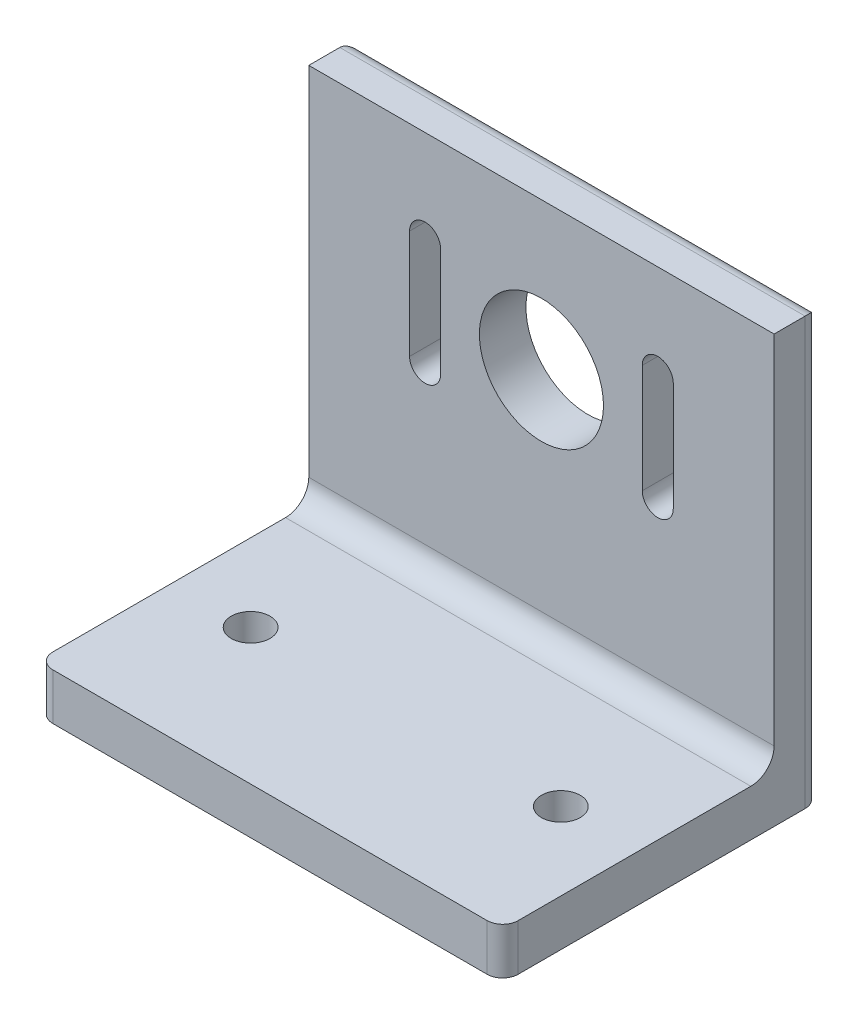
SolidWorks part; units mm, degrees
material "ABS"
ref_plane "Front Plane" through (0, 0, 0) normal (0, 0, 1) x (1, 0, 0)
ref_plane "Top Plane" through (0, 0, 0) normal (0, 1, 0) x (1, 0, 0)
ref_plane "Right Plane" through (0, 0, 0) normal (1, 0, 0) x (0, 0, -1)
sketch "Sketch2" plane through (0, 0, 0) normal (0, 1, 0) x (1, 0, 0)
  line L1 (-30, 17.5) -> (30, 17.5)
  line L2 (-30, 17.5) -> (-30, -17.5)
  line L3 (-30, -17.5) -> (30, -17.5)
  line L4 (30, 17.5) -> (30, -17.5)
  line L5 (-30, 17.5) -> (30, -17.5) construction
  line L6 (-30, -17.5) -> (30, 17.5) construction
  point P0 (0, 0)
  dimension "D1" = 60
  dimension "D2" = 35
extrude "Boss-Extrude1" add sketch "Sketch2" along normal blind 6
sketch "Sketch3" plane through (0, 0, -17.5) normal (0, 0, -1) x (-1, 0, 0)
  line L1 (-30, 0) -> (30, 0)
  line L2 (-30, 0) -> (-30, 55)
  line L3 (-30, 55) -> (30, 55)
  line L4 (30, 0) -> (30, 55)
  dimension "D1" = 60
  dimension "D2" = 55
extrude "Boss-Extrude2" add sketch "Sketch3" along normal blind 6
sketch "Sketch4" plane through (0, 0, -17.5) normal (0, 0, 1) x (1, 0, 0)
  line L0 (30, 6) -> (-30, 6) construction
  circle A0 centre (0, 36) radius 8
  point P4 (0, 6)
  dimension "D1" = 16
  dimension "D2" = 30
  dimension "D3" = 30
extrude "Cut-Extrude1" cut sketch "Sketch4" against normal through all
sketch "Sketch5" plane through (0, 0, -17.5) normal (0, 0, 1) x (1, 0, 0)
  line L0 (-15, 43) -> (-15, 29) construction
  line L1 (-13, 43) -> (-13, 29)
  line L2 (-17, 43) -> (-17, 29)
  line L3 (15, 43) -> (15, 29) construction
  line L4 (17, 43) -> (17, 29)
  line L5 (13, 43) -> (13, 29)
  arc A0 (-13, 43) -> (-17, 43) centre (-15, 43) ccw
  arc A1 (-17, 29) -> (-13, 29) centre (-15, 29) ccw
  arc A2 (17, 43) -> (13, 43) centre (15, 43) ccw
  arc A3 (13, 29) -> (17, 29) centre (15, 29) ccw
  point P2 (-15, 36)
  point P9 (15, 36)
  point P14 (-15, 45)
  point P15 (-15, 27)
  point P16 (15, 27)
  point P17 (15, 45)
  point P19 (-49.1657, 45.4135)
  dimension "D4" = 18
  dimension "D1" = 4
  dimension "D2" = 4
  dimension "D3" = 18
extrude "Cut-Extrude2" cut sketch "Sketch5" against normal through all
sketch "Sketch6" plane through (0, 6, 0) normal (0, 1, 0) x (1, 0, 0)
  line L0 (-30, 17.5) -> (-30, -17.5) construction
  line L1 (30, -17.5) -> (30, 17.5) construction
  circle A0 centre (-20, 0) radius 2.5
  circle A1 centre (20, 0) radius 2.5
  dimension "D1" = 5
  dimension "D2" = 5
  dimension "D3" = 10
  dimension "D4" = 10
extrude "Cut-Extrude3" cut sketch "Sketch6" against normal up to vertex (6 mm away) up to point (0, 0, 0)
fillet "Fillet1" radius 2 5 edges at (30, 3, 17.5) (-30, 3, 17.5) (0, 55, -23.5) (30, 27.5, -23.5) (-30, 27.5, -23.5)
fillet "Fillet2" radius 3 1 edges at (0, 6, -17.5)
